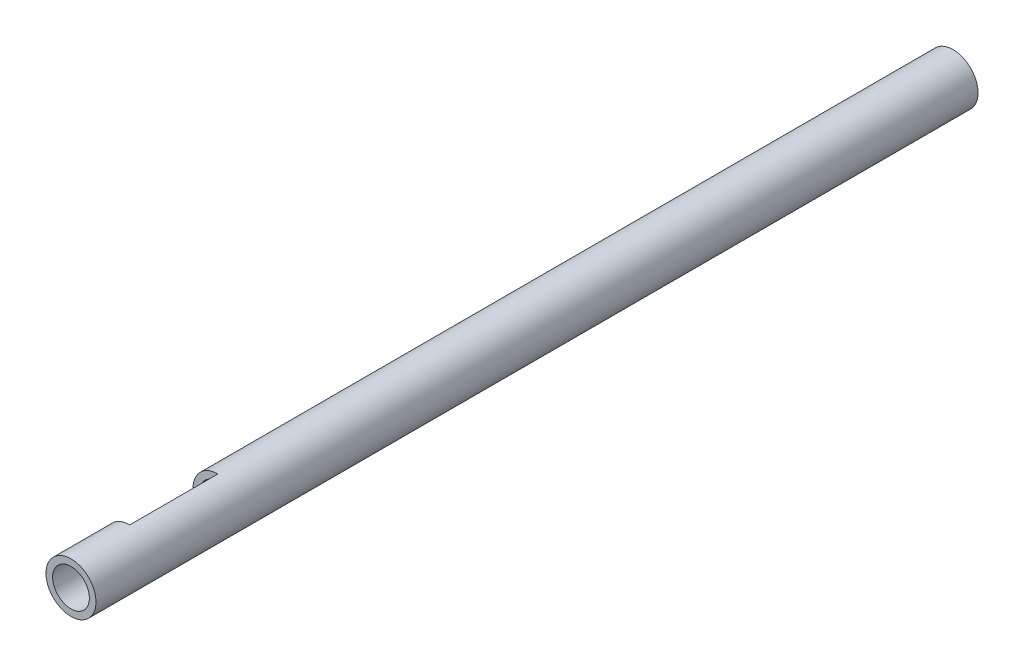
SolidWorks part; units mm, degrees
ref_plane "Front Plane" through (0, 0, 0) normal (0, 0, 1) x (1, 0, 0)
ref_plane "Top Plane" through (0, 0, 0) normal (0, 1, 0) x (1, 0, 0)
ref_plane "Right Plane" through (0, 0, 0) normal (1, 0, 0) x (0, 0, -1)
sketch "Sketch1" plane through (0, 0, 0) normal (1, 0, 0) x (0, 0, -1)
  line L0 (0, 0) -> (-101.6858, 0) construction
  line L2 (0, 17) -> (-600, 17)
  line L3 (0, 17) -> (0, 12.5)
  line L4 (0, 12.5) -> (-600, 12.5)
  line L5 (-600, 17) -> (-600, 12.5)
  dimension "D1" = 600
  dimension "D2" = 25
  dimension "D3" = 34
revolve "Revolve1" add sketch "Sketch1" angle 360 about L0
sketch "Sketch2" plane through (0, 0, 0) normal (0, 1, 0) x (1, 0, 0)
  line L0 (68, -472.5) -> (17, -472.5) construction
  line L1 (-37.7148, -587.5) -> (0, -587.5) construction
  line L2 (-37.7148, -587.5) -> (-37.7148, -472.5) construction
  line L3 (-37.7148, -472.5) -> (0, -472.5) construction
  line L4 (0, -587.5) -> (0, -472.5) construction
  line L7 (-37.7148, -500) -> (0, -500)
  line L8 (-37.7148, -500) -> (-37.7148, -560)
  line L9 (-37.7148, -560) -> (0, -560)
  line L10 (0, -500) -> (0, -560)
  line L11 (68, -587.5) -> (17, -587.5) construction
  point P13 (-37.7148, -530)
  dimension "D1" = 60
extrude "Cut-Extrude1" cut sketch "Sketch2" against normal through all and the other way through all
